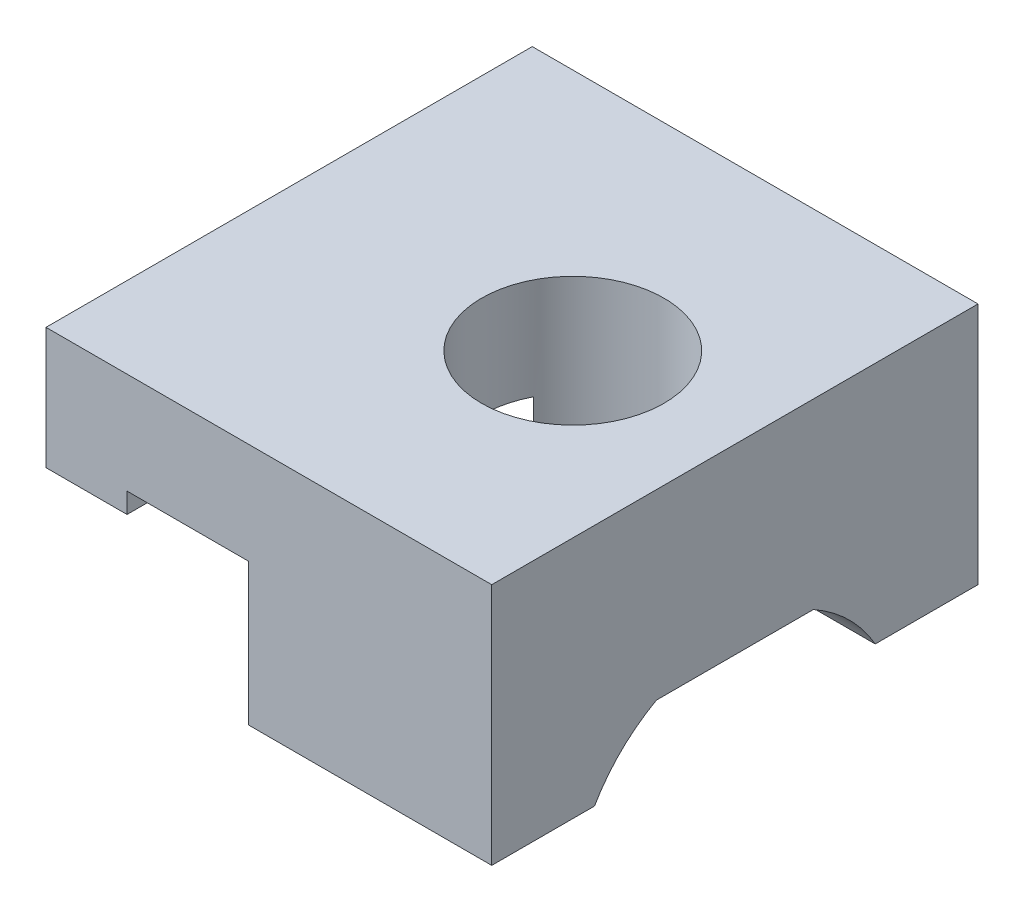
SolidWorks part; units mm, degrees
ref_plane "Front Plane" through (0, 0, 0) normal (0, 0, 1) x (1, 0, 0)
ref_plane "Top Plane" through (0, 0, 0) normal (0, 1, 0) x (1, 0, 0)
ref_plane "Right Plane" through (0, 0, 0) normal (1, 0, 0) x (0, 0, -1)
sketch "Sketch1" plane through (0, 0, 0) normal (1, 0, 0) x (0, 0, -1)
  line L0 (6, -6) -> (6, 0)
  line L1 (6, 0) -> (-6, 0)
  line L2 (-6, 0) -> (-6, -6)
  line L3 (-6, -6) -> (-3.4641, -6)
  line L4 (-1.9365, -4.5) -> (1.9365, -4.5)
  line L9 (3.4641, -6) -> (6, -6)
  arc A0 (3.4641, -6) -> (1.9365, -4.5) centre (0, -8) ccw
  arc A1 (-1.9365, -4.5) -> (-3.4641, -6) centre (0, -8) ccw
  dimension "MSM_97" = 4
  dimension "MSM_95" = 12
  dimension "FIX_1" = 6
  dimension "FIX_2" = 4.5
  dimension "MSM_96" = 8
extrude "Boss-Extrude1" add sketch "Sketch1" along normal blind 4 and the other way blind 7
sketch "Sketch2" plane through (0, 0, 0) normal (0, 0, 1) x (1, 0, 0)
  line L2 (-7, -3) -> (-5, -3)
  line L3 (-5, -3) -> (-5, -2.5)
  line L4 (-5, -2.5) -> (-2, -2.5)
  line L5 (-2, -2.5) -> (-2, -6)
  line L8 (-7, -3) -> (-7, -6)
  line L9 (-7, -6) -> (-2, -6)
  dimension "FIX_4" = 7
  dimension "FIX_5" = 6
  dimension "FIX_6" = 3
  dimension "FIX_7" = 2
  dimension "FIX_8" = 2.5
  dimension "FIX_9" = 5
extrude "Cut-Extrude1" cut sketch "Sketch2" against normal through all and the other way through all
sketch "Sketch3" plane through (0, 0, 0) normal (0, 1, 0) x (1, 0, 0)
  circle A0 centre (0, 0) radius 2.25
  dimension "MSM_99" = 4.5
extrude "Cut-Extrude2" cut sketch "Sketch3" against normal through all
